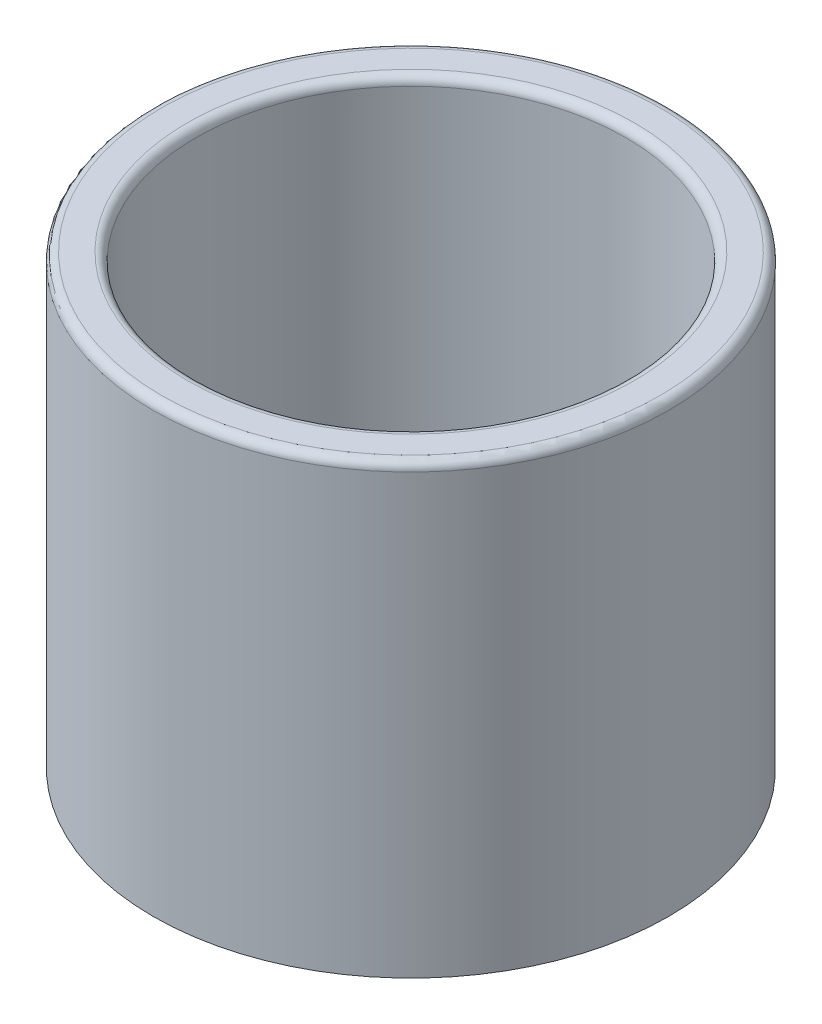
SolidWorks part; units mm, degrees
ref_plane "Front Plane" through (0, 0, 0) normal (0, 0, 1) x (1, 0, 0)
ref_plane "Top Plane" through (0, 0, 0) normal (0, 1, 0) x (1, 0, 0)
ref_plane "Right Plane" through (0, 0, 0) normal (1, 0, 0) x (0, 0, -1)
sketch "Sketch1" plane through (0, 0, 0) normal (0, 1, 0) x (1, 0, 0)
  circle A0 centre (0, 0) radius 25
  circle A1 centre (0, 0) radius 30
  dimension "D2" = 50
  dimension "D1" = 5
extrude "Boss-Extrude1" add sketch "Sketch1" along normal blind 50
sketch "Sketch2" plane through (0, 0, 0) normal (0, -1, 0) x (1, 0, 0)
  line L0 (-30, 0) -> (30, 0) construction
  line L1 (30, 0) -> (0, 30) construction
  line L2 (0, 30) -> (0, -30) construction
  circle A0 centre (0, 0) radius 30
extrude "Boss-Extrude2" add sketch "Sketch2" along normal blind 2
fillet "Fillet1" radius 1 3 edges at (0, 0, 25) (0, 50, 25) (0, 50, 30)
